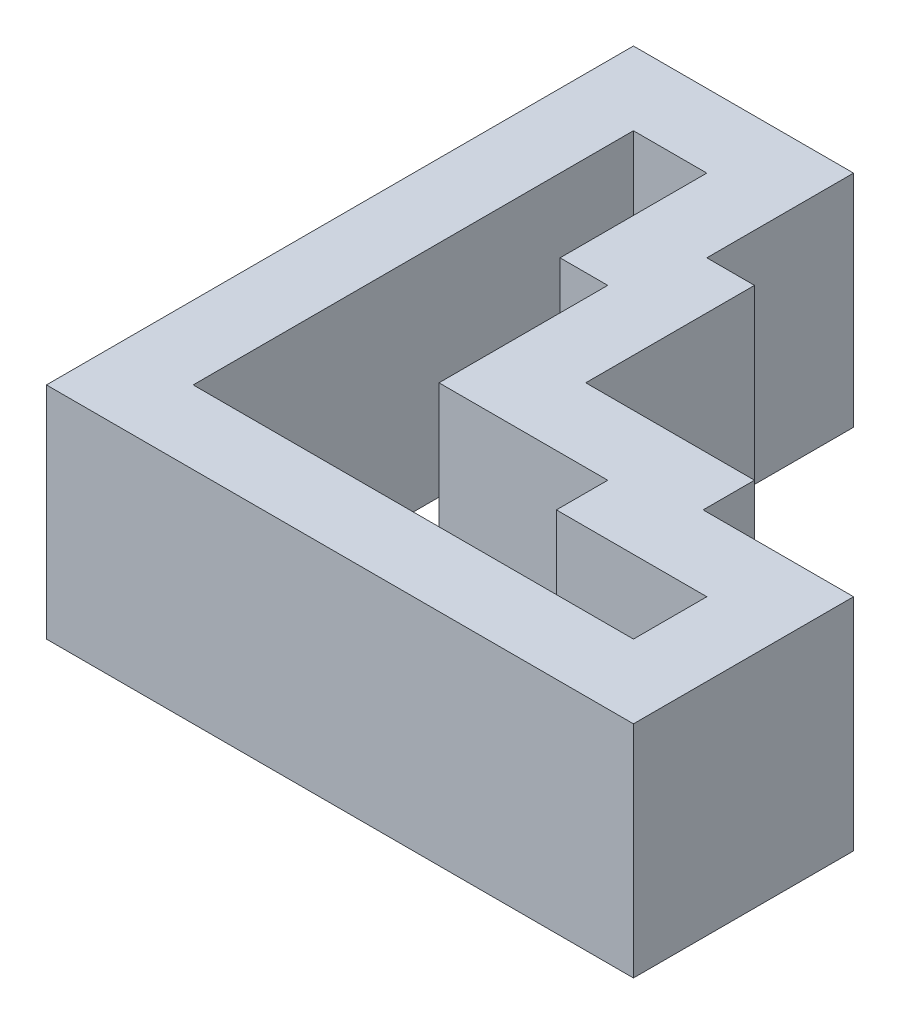
SolidWorks part; units mm, degrees
material "3.0205 (EN-AW 1200)"
ref_plane "前视基准面" through (0, 0, 0) normal (0, 0, 1) x (1, 0, 0)
ref_plane "上视基准面" through (0, 0, 0) normal (0, 1, 0) x (1, 0, 0)
ref_plane "右视基准面" through (0, 0, 0) normal (1, 0, 0) x (0, 0, -1)
other "Configuration Table"
sketch "草图1" plane through (0, 0, 0) normal (0, 1, 0) x (1, 0, 0)
  line L0 (0, 0) -> (60, 0)
  line L1 (60, 0) -> (60, 10)
  line L2 (60, 10) -> (39.5, 10)
  line L3 (39.5, 10) -> (39.5, 17)
  line L4 (39.5, 17) -> (16.5, 17)
  line L5 (16.5, 17) -> (16.5, 40)
  line L6 (16.5, 40) -> (10, 40)
  line L7 (10, 40) -> (10, 60)
  line L8 (10, 60) -> (0, 60)
  line L9 (0, 60) -> (0, 0)
  dimension "D1" = 60
  dimension "D2" = 60
  dimension "D3" = 10
  dimension "D4" = 10
  dimension "D5" = 20.5
  dimension "D6" = 7
  dimension "D7" = 23
  dimension "D8" = 23
extrude "拉伸-薄壁1" add sketch "草图1" along normal blind 30 thin
